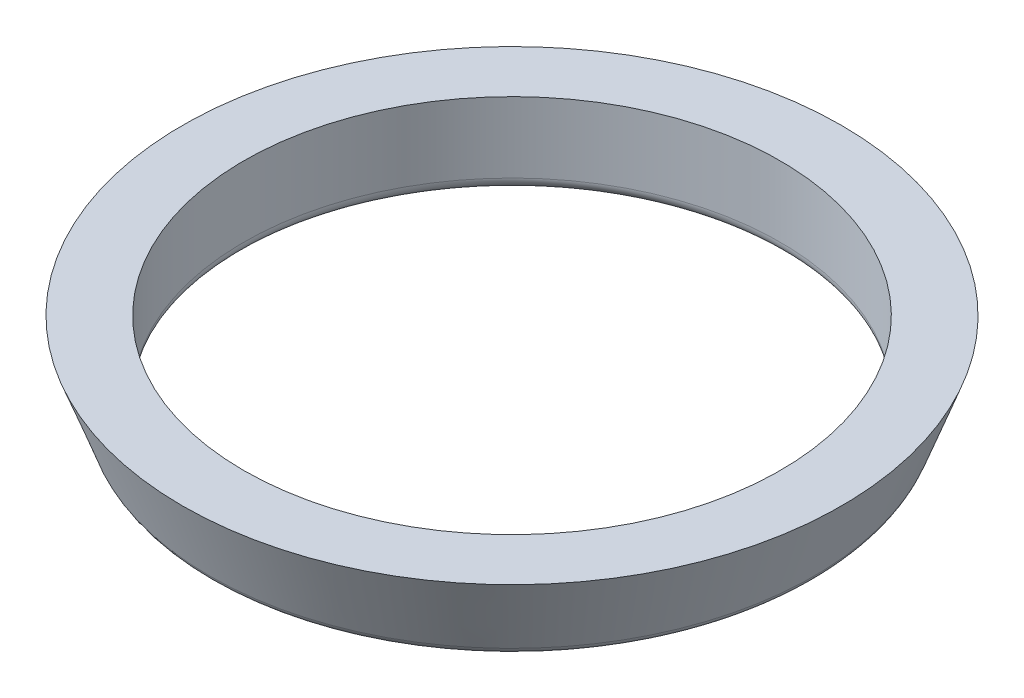
SolidWorks part; units mm, degrees
material "ABS"
ref_plane "Front" through (0, 0, 0) normal (0, 0, 1) x (1, 0, 0)
ref_plane "Top" through (0, 0, 0) normal (0, 1, 0) x (1, 0, 0)
ref_plane "Right" through (0, 0, 0) normal (1, 0, 0) x (0, 0, -1)
sketch "Sketch1" plane through (0, 0, 0) normal (0, 1, 0) x (1, 0, 0)
  circle A0 centre (0, 0) radius 107.5
  dimension "D1" = 215
sketch "Sketch2" plane through (0, 0, 0) normal (1, 0, 0) x (0, 0, -1)
  line L0 (-107.5, 0) -> (-98.4669, -24.3893)
  line L1 (107.5, 0) -> (-107.5, 0) construction
  line L2 (-94.7159, -27) -> (-91.5, -27)
  line L3 (-87.5, -23) -> (-87.5, 0)
  line L4 (-87.5, 0) -> (-107.5, 0)
  line L5 (0, 0) -> (0, -27.9852) construction
  arc A0 (-91.5, -27) -> (-87.5, -23) centre (-91.5, -23) ccw
  arc A1 (-98.4669, -24.3893) -> (-94.7159, -27) centre (-94.7159, -23) ccw
  point P8 (-87.5, -27)
  point P11 (-97.5, -27)
  dimension "D4" = 4
  dimension "D1" = 20
  dimension "D2" = 27
  dimension "D3" = 10
revolve "Revolve1" add sketch "Sketch2" angle 360 about L5
